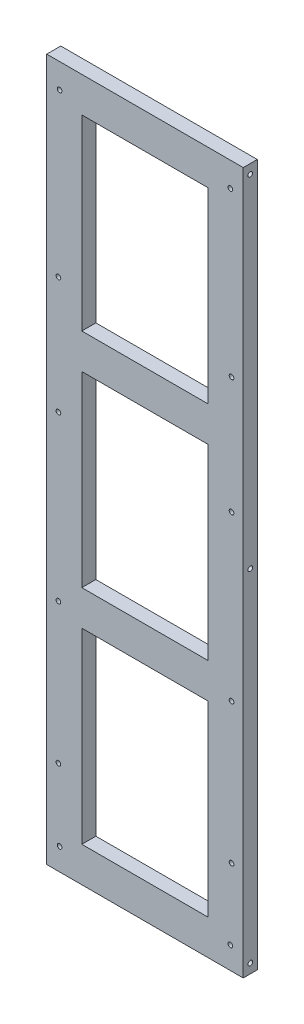
SolidWorks part; units mm, degrees
material "Alumina"
ref_plane "Front Plane" through (0, 0, 0) normal (0, 0, 1) x (1, 0, 0)
ref_plane "Top Plane" through (0, 0, 0) normal (0, 1, 0) x (1, 0, 0)
ref_plane "Right Plane" through (0, 0, 0) normal (1, 0, 0) x (0, 0, -1)
sketch "Sketch1" plane through (0, 0, 0) normal (0, 0, 1) x (1, 0, 0)
  line L0 (27, 135) -> (27, 55)
  line L9 (-42, -150) -> (42, -150)
  line L10 (-42, -150) -> (-42, 150)
  line L11 (-42, 150) -> (42, 150)
  line L12 (42, -150) -> (42, 150)
  line L13 (0, 0) -> (0, 40) construction
  line L15 (-27, -135) -> (27, -135)
  line L16 (-27, -135) -> (-27, -55)
  line L17 (-27, 135) -> (27, 135)
  line L21 (-27, 55) -> (27, 55)
  line L23 (-27, 40) -> (27, 40)
  line L25 (-27, -40) -> (27, -40)
  line L27 (-27, -55) -> (27, -55)
  line L33 (27, 40) -> (27, -40)
  line L34 (-27, 55) -> (-27, 135)
  line L35 (-27, -40) -> (-27, 40)
  line L36 (27, -55) -> (27, -135)
  dimension "D1" = 84
  dimension "D2" = 300
  dimension "D3" = 54
  dimension "D4" = 270
  dimension "D5" = 15
  dimension "D6" = 80
  dimension "D7" = 15
  dimension "D8" = 80
  dimension "D9" = 15
  dimension "D10" = 15
  dimension "D11" = 80
  dimension "D12" = 40
  dimension "D13" = 15
extrude "Boss-Extrude1" add sketch "Sketch1" along normal blind 6
sketch "Sketch2" plane through (42, 0, 0) normal (1, 0, 0) x (0, 0, -1)
  line L0 (-6, 150) -> (0, 150) construction
  line L1 (-6, -150) -> (-6, 150) construction
  line L3 (-3, 146) -> (-3, 0) construction
  circle A0 centre (-3, 146) radius 1
  circle A4 centre (-3, 0) radius 1
  circle A5 centre (-3, -146) radius 1
  circle A6 centre (-3, -292) radius 1
  dimension "D1" = 4
  dimension "D3" = 2
  dimension "D4" = 3
  dimension "D2" = 4
  dimension "D5" = 146
extrude "Cut-Extrude1" cut sketch "Sketch2" against normal blind 10
mirror "Mirror1" about plane through (0, 0, 0) normal (1, 0, 0) of "Cut-Extrude1"
sketch "Sketch4" plane through (0, 0, 6) normal (0, 0, 1) x (1, 0, 0)
  line L0 (-42, -150) -> (-42, 150) construction
  line L1 (-42, 150) -> (-42, -150) construction
  line L2 (-42, 150) -> (42, 150) construction
  line L3 (0, -3.3) -> (0, 3.3) construction
  line L8 (-37, 70) -> (-37, -51) construction
  circle A8 centre (-37, 70) radius 1
  circle A41 centre (-37, 20) radius 1
  circle A43 centre (-37, -50) radius 1
  circle A54 centre (-37, -110) radius 1
  circle A55 centre (37, -110) radius 1
  circle A56 centre (37, -50) radius 1
  circle A57 centre (37, 20) radius 1
  circle A58 centre (37, 70) radius 1
  dimension "D4" = 2
  dimension "D3" = 5
  dimension "D6" = 60
  dimension "D14" = 2
  dimension "D16" = 2
  dimension "D19" = 50
  dimension "D22" = 2
  dimension "D25" = 70
  dimension "D5" = 80
  dimension "D9" = 5
extrude "Cut-Extrude3" cut sketch "Sketch4" against normal blind 10
sketch "Sketch5" plane through (0, 0, 6) normal (0, 0, 1) x (1, 0, 0)
  line L0 (-36.5, 139.5) -> (36.5, 139.5) construction
  line L1 (36.5, 139.5) -> (36.5, -140.5) construction
  line L2 (36.5, -140.5) -> (-36.5, -140.5) construction
  line L3 (-36.5, -140.5) -> (-36.5, 139.5) construction
  line L4 (-42, 150) -> (-42, -150) construction
  line L5 (42, 150) -> (-42, 150) construction
  line L6 (42, -150) -> (42, 150) construction
  line L7 (-42, -150) -> (42, -150) construction
  circle A0 centre (-36.5, -140.5) radius 1
  circle A1 centre (36.5, -140.5) radius 1
  circle A2 centre (-36.5, 139.5) radius 1
  circle A3 centre (36.5, 139.5) radius 1
  dimension "D5" = 2
  dimension "D6" = 2
  dimension "D7" = 2
  dimension "D8" = 2
  dimension "D1" = 5.5
  dimension "D2" = 10.5
  dimension "D3" = 5.5
  dimension "D4" = 9.5
extrude "Cut-Extrude4" cut sketch "Sketch5" against normal blind 10
